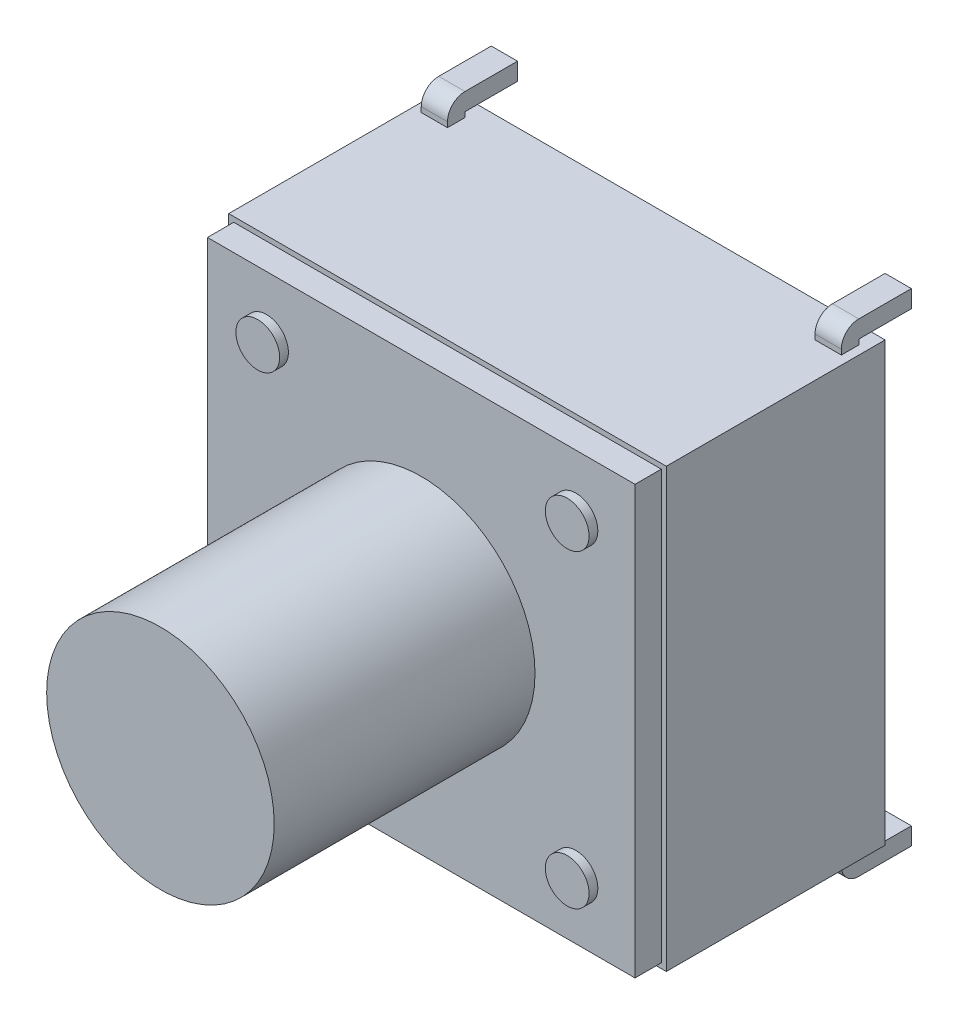
SolidWorks part; units mm, degrees
ref_plane "Front Plane" through (0, 0, 0) normal (0, 0, 1) x (1, 0, 0)
ref_plane "Top Plane" through (0, 0, 0) normal (0, 1, 0) x (1, 0, 0)
ref_plane "Right Plane" through (0, 0, 0) normal (1, 0, 0) x (0, 0, -1)
ref_plane "Plane1" through (0, 0, 3.175) normal (0, 0, 1) x (1, 0, 0)
sketch "Sketch1" plane through (0, 0, 3.175) normal (0, 0, 1) x (1, 0, 0)
  line L0 (-3.175, 3.175) -> (-3.175, -3.175)
  line L1 (-3.175, -3.175) -> (3.175, -3.175)
  line L2 (3.175, -3.175) -> (3.175, 3.175)
  line L3 (3.175, 3.175) -> (-3.175, 3.175)
extrude "Boss-Extrude1" add sketch "Sketch1" against normal blind 3.175
ref_plane "Plane2" through (0, 0, 3.556) normal (0, 0, 1) x (1, 0, 0)
sketch "Sketch2" plane through (0, 0, 3.556) normal (0, 0, 1) x (1, 0, 0)
  line L0 (3.1021, 3.1021) -> (-3.1021, 3.1021)
  line L1 (-3.1021, 3.1021) -> (-3.1021, -3.1021)
  line L2 (-3.1021, -3.1021) -> (3.1021, -3.1021)
  line L3 (3.1021, -3.1021) -> (3.1021, 3.1021)
extrude "Boss-Extrude2" add sketch "Sketch2" against normal up to surface (0.381 mm away) up to face at (0, 0, 3.175)
ref_plane "Plane3" through (2.667, 0, 0) normal (-1, 0, 0) x (0, -1, 0)
sketch "Sketch3" plane through (2.667, 0, 0) normal (-1, 0, 0) x (0, -1, 0)
  line L0 (3.2489, 0.254) -> (3.2489, -0.508)
  line L1 (3.2489, -0.508) -> (3.5029, -0.508)
  line L2 (3.5029, -0.508) -> (3.5029, 0.254)
  line L3 (3.2489, 0.508) -> (3.175, 0.508)
  line L4 (3.175, 0.508) -> (3.175, 0.254)
  line L5 (3.175, 0.254) -> (3.2489, 0.254)
  line L6 (-3.5029, 0.254) -> (-3.5029, -0.508)
  line L7 (-3.5029, -0.508) -> (-3.2489, -0.508)
  line L8 (-3.2489, -0.508) -> (-3.2489, 0.254)
  line L9 (-3.2489, 0.254) -> (-3.175, 0.254)
  line L10 (-3.175, 0.254) -> (-3.175, 0.508)
  line L11 (-3.175, 0.508) -> (-3.2489, 0.508)
  arc A0 (3.5029, 0.254) -> (3.2489, 0.508) centre (3.2489, 0.254) ccw
  arc A1 (-3.2489, 0.508) -> (-3.5029, 0.254) centre (-3.2489, 0.254) ccw
extrude "Boss-Extrude3" add sketch "Sketch3" against normal blind 0.381
ref_plane "Plane4" through (-2.667, 0, 0) normal (1, 0, 0) x (0, 0, -1)
sketch "Sketch4" plane through (-2.667, 0, 0) normal (1, 0, 0) x (0, 0, -1)
  line L0 (-0.254, -3.5029) -> (0.508, -3.5029)
  line L1 (0.508, -3.5029) -> (0.508, -3.2489)
  line L2 (0.508, -3.2489) -> (-0.254, -3.2489)
  line L3 (-0.254, -3.2489) -> (-0.254, -3.175)
  line L4 (-0.254, -3.175) -> (-0.508, -3.175)
  line L5 (-0.508, -3.175) -> (-0.508, -3.2489)
  line L6 (-0.508, 3.2489) -> (-0.508, 3.175)
  line L7 (-0.508, 3.175) -> (-0.254, 3.175)
  line L8 (-0.254, 3.175) -> (-0.254, 3.2489)
  line L9 (-0.254, 3.2489) -> (0.508, 3.2489)
  line L10 (0.508, 3.2489) -> (0.508, 3.5029)
  line L11 (0.508, 3.5029) -> (-0.254, 3.5029)
  arc A0 (-0.508, -3.2489) -> (-0.254, -3.5029) centre (-0.254, -3.2489) ccw
  arc A1 (-0.254, 3.5029) -> (-0.508, 3.2489) centre (-0.254, 3.2489) ccw
extrude "Boss-Extrude4" add sketch "Sketch4" against normal blind 0.381
ref_plane "Plane5" through (0, 0, 3.683) normal (0, 0, 1) x (1, 0, 0)
sketch "Sketch5" plane through (0, 0, 3.683) normal (0, 0, 1) x (1, 0, 0)
  circle A0 centre (2.2451, -2.2451) radius 0.3175
  circle A1 centre (-2.2451, -2.2451) radius 0.3175
  circle A2 centre (-2.2451, 2.2451) radius 0.3175
  circle A3 centre (2.2451, 2.2451) radius 0.3175
extrude "Boss-Extrude5" add sketch "Sketch5" against normal up to next
ref_plane "Plane6" through (0, 0, 7.3406) normal (0, 0, 1) x (1, 0, 0)
sketch "Sketch6" plane through (0, 0, 7.3406) normal (0, 0, 1) x (1, 0, 0)
  circle A0 centre (0, 0) radius 1.651
extrude "Boss-Extrude6" add sketch "Sketch6" against normal up to surface (3.7846 mm away) up to face at (2.5626, 2.2451, 3.556)
